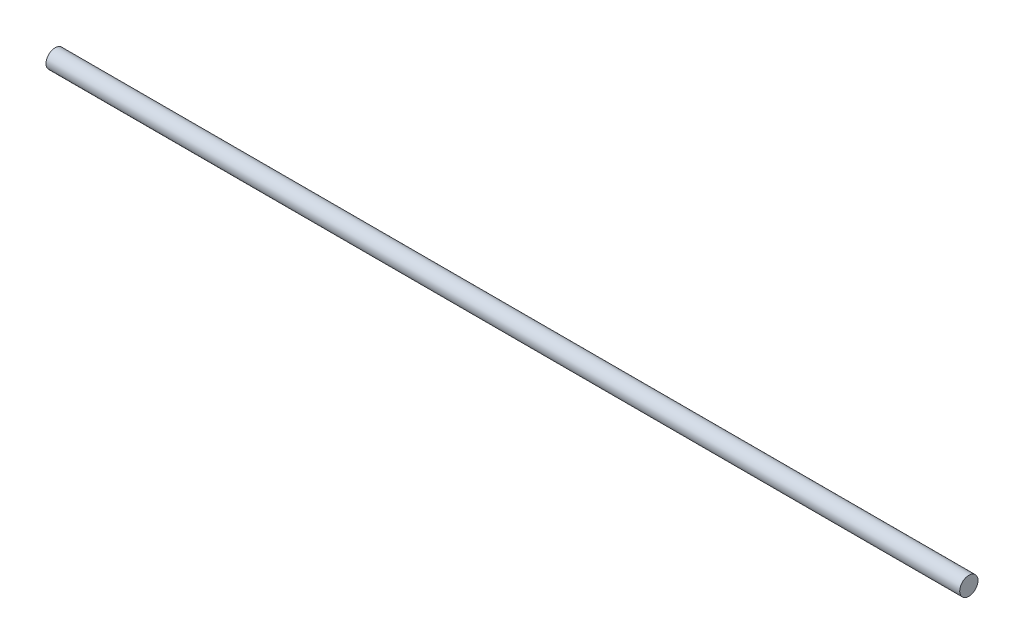
SolidWorks part; units mm, degrees
ref_plane "Front Plane" through (0, 0, 0) normal (0, 0, 1) x (1, 0, 0)
ref_plane "Top Plane" through (0, 0, 0) normal (0, 1, 0) x (1, 0, 0)
ref_plane "Right Plane" through (0, 0, 0) normal (1, 0, 0) x (0, 0, -1)
sketch "Sketch1" plane through (0, 0, 0) normal (1, 0, 0) x (0, 0, -1)
  circle A0 centre (0, 0) radius 0.5
extrude "Boss-Extrude1" add sketch "Sketch1" along normal blind 50
